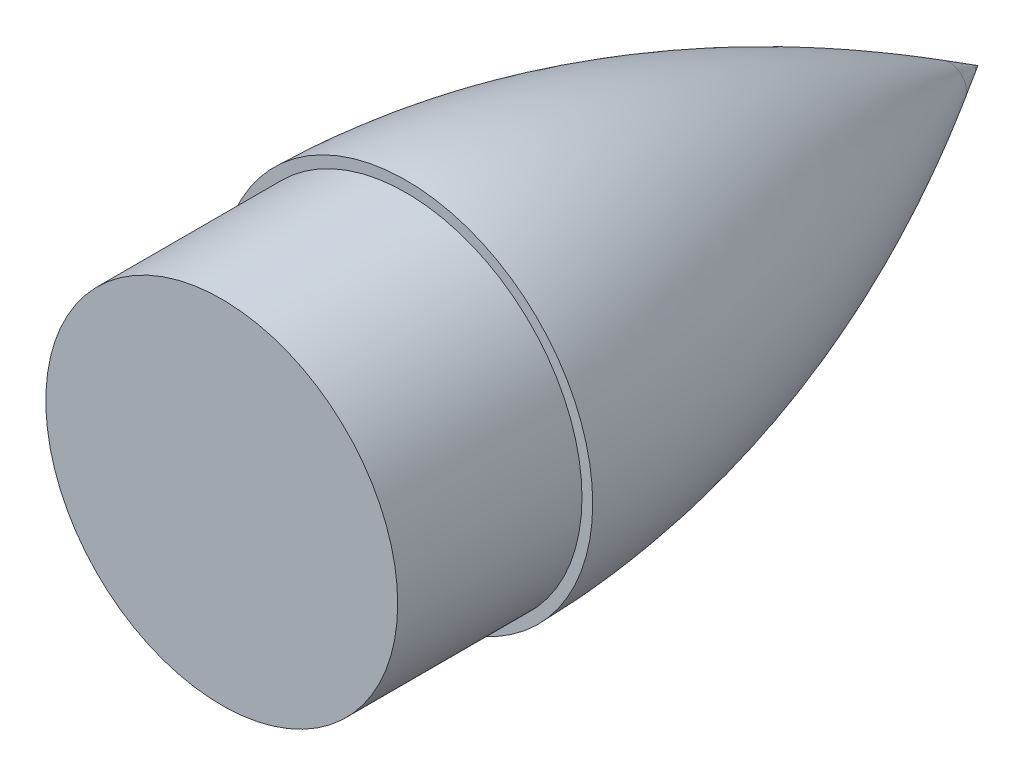
SolidWorks part; units mm, degrees
material "Плотность 1"
ref_plane "Спереди" through (0, 0, 0) normal (0, 0, 1) x (1, 0, 0)
ref_plane "Сверху" through (0, 0, 0) normal (0, 1, 0) x (1, 0, 0)
ref_plane "Справа" through (0, 0, 0) normal (1, 0, 0) x (0, 0, -1)
sketch "Эскиз1" plane through (0, 0, 0) normal (0, 1, 0) x (1, 0, 0)
  line L0 (0, 0) -> (0, 70.2694) construction
  line L1 (0, 0) -> (-21, 0) construction
  line L2 (-21, -18) -> (-21, -20)
  line L5 (-17.766, -20) -> (0, -20)
  line L6 (0, -20) -> (0, 70.2694)
  line L7 (-17.766, -20) -> (-21, -20)
  line L8 (-2, 66.8948) -> (0, 70.2694)
  line L9 (0, -20) -> (0, 80) construction
  line L10 (-21, 2) -> (-21, -18)
  line L11 (-22.2796, 2) -> (-21, 2)
  line L12 (-17.766, -18) -> (-2, -18) construction
  line L13 (-2, -18) -> (-2, 66.8948) construction
  line L14 (-17.766, -18) -> (-21, -18) construction
  line L15 (-25, 0) -> (0, 80) construction
  line L16 (-22.2796, 2) -> (-2, 66.8948) construction
  line L17 (-25, 0) -> (-23, 0) construction
  line L18 (-23, 0) -> (-23, -20) construction
  line L19 (-17.766, -20) -> (-23, -20) construction
  spline S2 degree 3 poles (-22.2796, 2) (-22.226, 4.6525) (-21.9225, 9.9335) (-20.5262, 20.5955) (-17.945, 31.3398) (-14.1728, 42.1868) (-10.7478, 50.3692) (-7.392, 57.2348) (-4.415, 62.7396) (-2.8132, 65.5226) (-2, 66.8948) knots 0.025818 0.025818 0.025818 0.025818 0.138043 0.250267 0.474716 0.58694 0.699165 0.811389 0.867501 0.923613 0.923613 0.923613 0.923613
revolve "Повернуть1" add sketch "Эскиз1" angle 360 about L6
